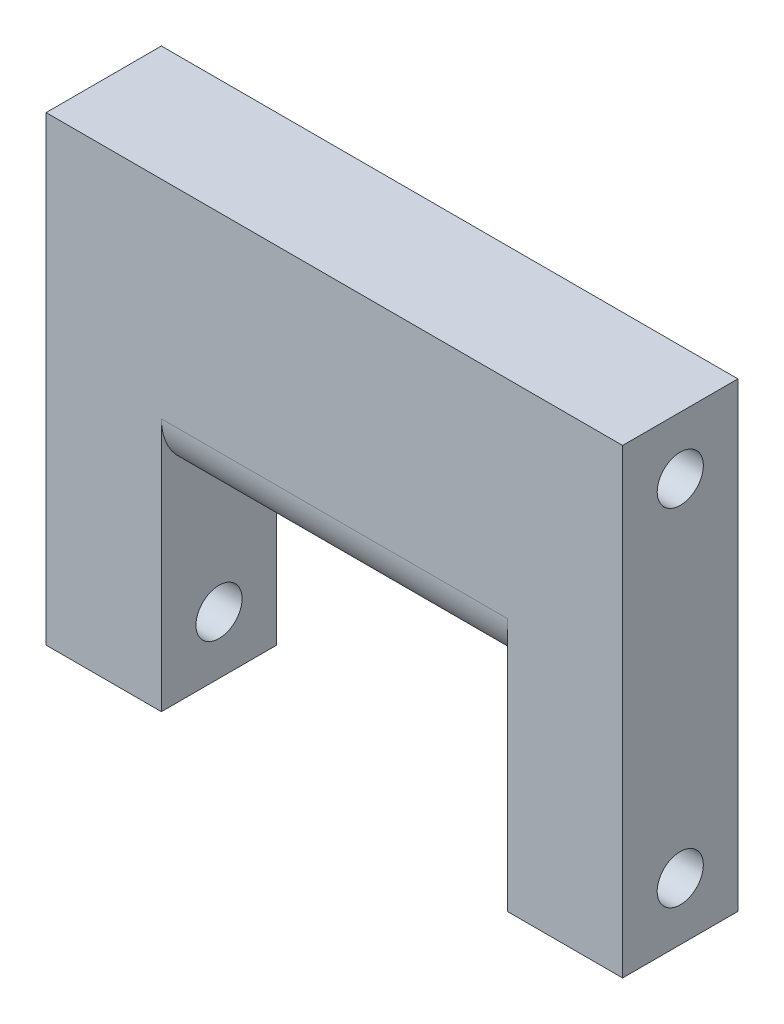
SolidWorks part; units mm, degrees
ref_plane "Front Plane" through (0, 0, 0) normal (0, 0, 1) x (1, 0, 0)
ref_plane "Top Plane" through (0, 0, 0) normal (0, 1, 0) x (1, 0, 0)
ref_plane "Right Plane" through (0, 0, 0) normal (1, 0, 0) x (0, 0, -1)
sketch "Sketch1" plane through (0, 0, 0) normal (0, 0, 1) x (1, 0, 0)
  line L0 (40, 0) -> (50, 0)
  line L1 (0, 0) -> (10, 0)
  line L2 (0, 0) -> (0, 40)
  line L3 (0, 40) -> (50, 40)
  line L4 (50, 0) -> (50, 40)
  line L6 (10, 0) -> (10, 17)
  line L7 (10, 17) -> (40, 17)
  line L8 (40, 0) -> (40, 17)
  dimension "D1" = 10
  dimension "D2" = 10
  dimension "D3" = 50
  dimension "D4" = 40
  dimension "D5" = 17
extrude "Boss-Extrude1" add sketch "Sketch1" along normal blind 10
sketch "Sketch2" plane through (50, 0, 0) normal (1, 0, 0) x (0, 0, -1)
  line L0 (-10, 0) -> (0, 0) construction
  line L1 (0, 0) -> (0, 40) construction
  circle A0 centre (-5, 5) radius 2
  dimension "D3" = 4
  dimension "D1" = 5
  dimension "D2" = 5
extrude "Cut-Extrude1" cut sketch "Sketch2" against normal through all
fillet "Fillet1" radius 5 1 edges at (25, 17, 10)
sketch "Sketch3" plane through (0, 0, 0) normal (-1, 0, 0) x (0, 0, 1)
  line L0 (10, 40) -> (0, 40) construction
  line L1 (0, 40) -> (0, 0) construction
  circle A0 centre (5, 35) radius 2
  dimension "D3" = 4
  dimension "D1" = 5
  dimension "D2" = 5
extrude "Cut-Extrude2" cut sketch "Sketch3" against normal through all
